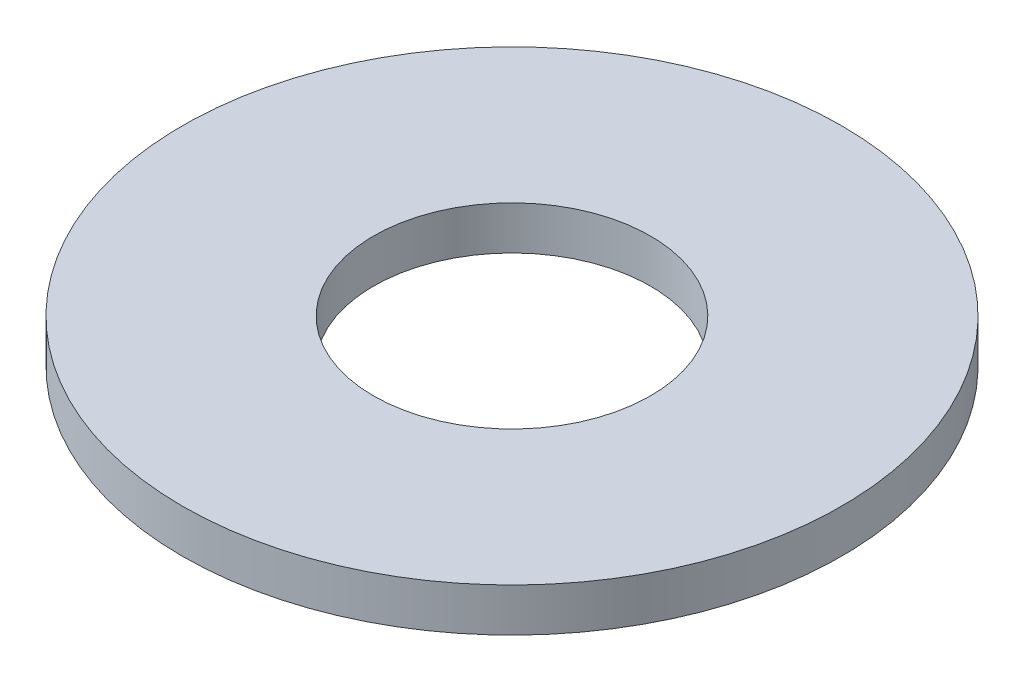
SolidWorks part; units mm, degrees
ref_plane "Front Plane" through (0, 0, 0) normal (0, 0, 1) x (1, 0, 0)
ref_plane "Top Plane" through (0, 0, 0) normal (0, 1, 0) x (1, 0, 0)
ref_plane "Right Plane" through (0, 0, 0) normal (1, 0, 0) x (0, 0, -1)
sketch "Sketch1" plane through (0, 0, 0) normal (0, 1, 0) x (1, 0, 0)
  line L0 (0, 37.95) -> (0, 15.95) construction
  circle A0 centre (0, 0) radius 37.95
  circle A1 centre (0, 0) radius 15.95
  dimension "D1" = 75.9
  dimension "D2" = 31.9
extrude "Boss-Extrude1" add sketch "Sketch1" along normal blind 5
